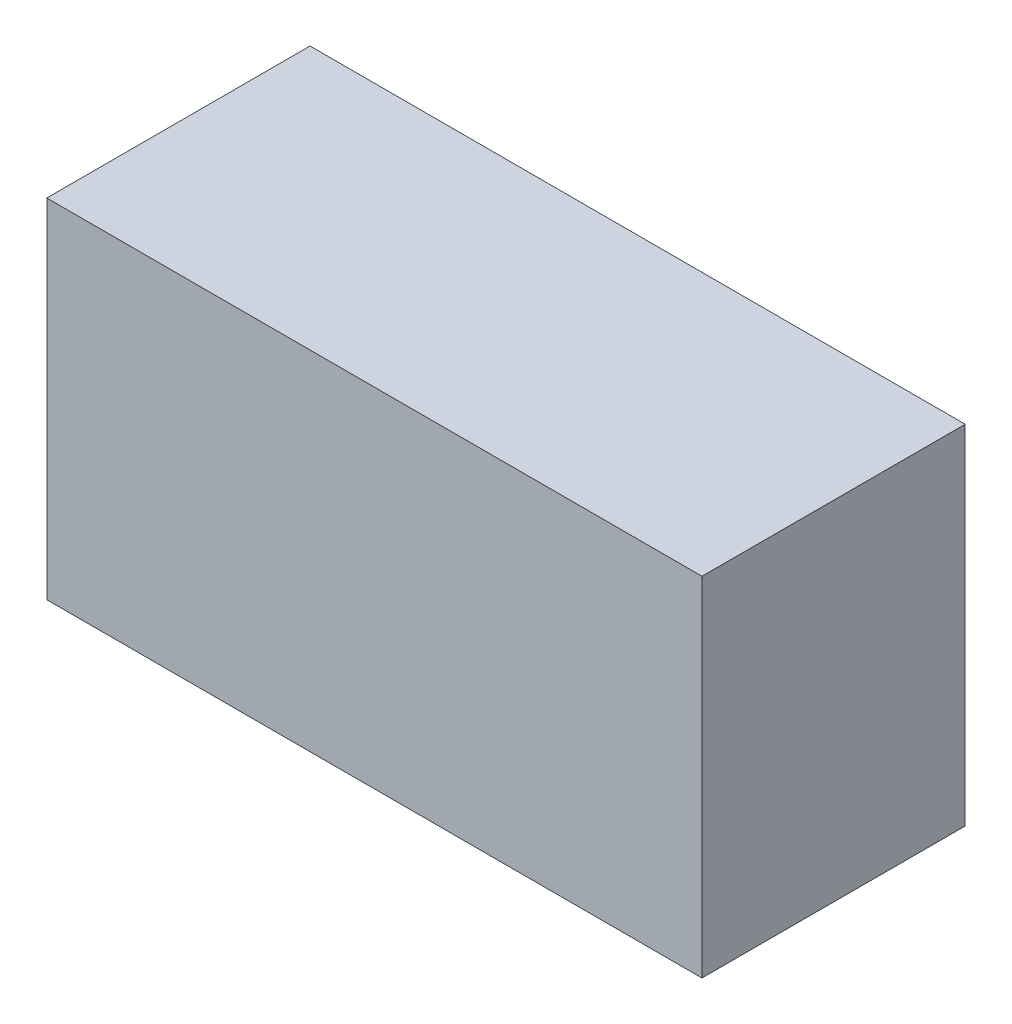
SolidWorks part; units mm, degrees
ref_plane "Front Plane" through (0, 0, 0) normal (0, 0, 1) x (1, 0, 0)
ref_plane "Top Plane" through (0, 0, 0) normal (0, 1, 0) x (1, 0, 0)
ref_plane "Right Plane" through (0, 0, 0) normal (1, 0, 0) x (0, 0, -1)
sketch "Sketch1" plane through (0, 0, 0) normal (0, 0, 1) x (1, 0, 0)
  line L0 (-1.2444, 0.6608) -> (1.2444, 0.6608)
  line L1 (1.2444, 0.6608) -> (1.2444, -0.6608)
  line L2 (1.2444, -0.6608) -> (-1.2444, -0.6608)
  line L3 (-1.2444, -0.6608) -> (-1.2444, 0.6608)
extrude "Component_Outline" add sketch "Sketch1" along normal blind 1 separate body
sketch3d "3DSketch1"
  line L0 (0, 0, 0) -> (1, 0, 0)
  line L1 (0, 0, 0) -> (0, 1, 0)
  line L2 (0, 0, 0) -> (0, 0, 1)
  point P0 (0, 0, 0)
